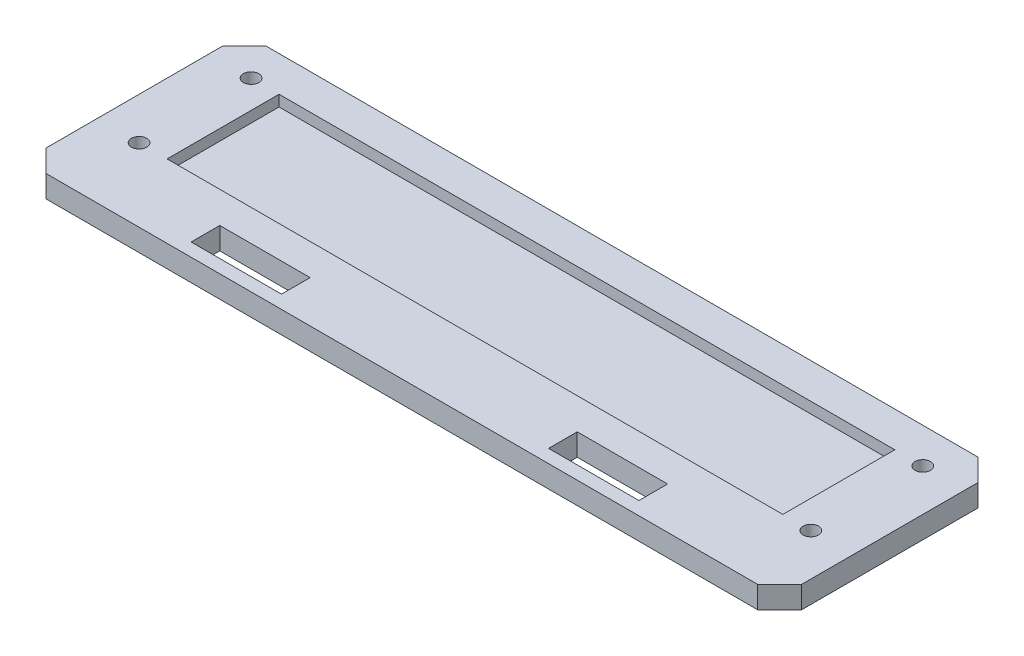
SolidWorks part; units mm, degrees
ref_plane "Front Plane" through (0, 0, 0) normal (0, 0, 1) x (1, 0, 0)
ref_plane "Top Plane" through (0, 0, 0) normal (0, 1, 0) x (1, 0, 0)
ref_plane "Right Plane" through (0, 0, 0) normal (1, 0, 0) x (0, 0, -1)
sketch "Sketch1" plane through (0, 0, 0) normal (0, 1, 0) x (1, 0, 0)
  line L1 (-85.725, -25) -> (85.725, -25)
  line L2 (-85.725, -25) -> (-85.725, 25)
  line L3 (-85.725, 25) -> (85.725, 25)
  line L4 (85.725, -25) -> (85.725, 25)
  line L5 (-85.725, -25) -> (85.725, 25) construction
  line L6 (-85.725, 25) -> (85.725, -25) construction
  circle A0 centre (-76.2, 17) radius 1.75
  circle A1 centre (76.2, 17) radius 1.75
  circle A2 centre (-76.2, -8.4) radius 1.75
  circle A3 centre (76.2, -8.4) radius 1.75
  point P0 (0, 0)
  dimension "D3" = 3.5
  dimension "D4" = 3.5
  dimension "D5" = 3.5
  dimension "D6" = 3.5
  dimension "D7" = 152.4
  dimension "D8" = 152.4
  dimension "D9" = 25.4
  dimension "D10" = 9.525
  dimension "D11" = 9.525
  dimension "D12" = 8
  dimension "D13" = 8
  dimension "D14" = 25.4
  dimension "D1" = 171.45
  dimension "D2" = 50
extrude "Boss-Extrude1" add sketch "Sketch1" along normal blind 5
chamfer "Chamfer1" distance 5 angle 45 4 edges at (85.725, 2.5, 25) (-85.725, 2.5, 25) (-85.725, 2.5, -25) (85.725, 2.5, -25)
sketch "Sketch2" plane through (0, 5, 0) normal (0, 1, 0) x (1, 0, 0)
  line L1 (-69.85, 17) -> (69.85, 17)
  line L2 (-69.85, 17) -> (-69.85, -8.4)
  line L3 (-69.85, -8.4) -> (69.85, -8.4)
  line L4 (69.85, 17) -> (69.85, -8.4)
  circle A0 centre (-76.2, 17) radius 1.75 construction
  dimension "D1" = 25.4
  dimension "D2" = 0
  dimension "D3" = 139.7
  dimension "D4" = 6.35
extrude "Cut-Extrude1" cut sketch "Sketch2" against normal blind 2.5
sketch "Sketch3" plane through (0, 5, 0) normal (0, 1, 0) x (1, 0, 0)
  line L0 (85.725, -20) -> (85.725, 20) construction
  line L1 (50.8, -22) -> (30.3, -22)
  line L2 (50.8, -22) -> (50.8, -15.5)
  line L3 (50.8, -15.5) -> (30.3, -15.5)
  line L4 (30.3, -22) -> (30.3, -15.5)
  line L5 (-30.3, -22) -> (-50.8, -22)
  line L6 (-30.3, -22) -> (-30.3, -15.5)
  line L7 (-30.3, -15.5) -> (-50.8, -15.5)
  line L8 (-50.8, -22) -> (-50.8, -15.5)
  line L9 (-80.725, -25) -> (80.725, -25) construction
  dimension "D1" = 20.5
  dimension "D2" = 6.5
  dimension "D3" = 20.5
  dimension "D4" = 6.5
  dimension "D5" = 101.6
  dimension "D6" = 34.925
  dimension "D7" = 3
  dimension "D8" = 3
extrude "Cut-Extrude2" cut sketch "Sketch3" against normal blind 15
